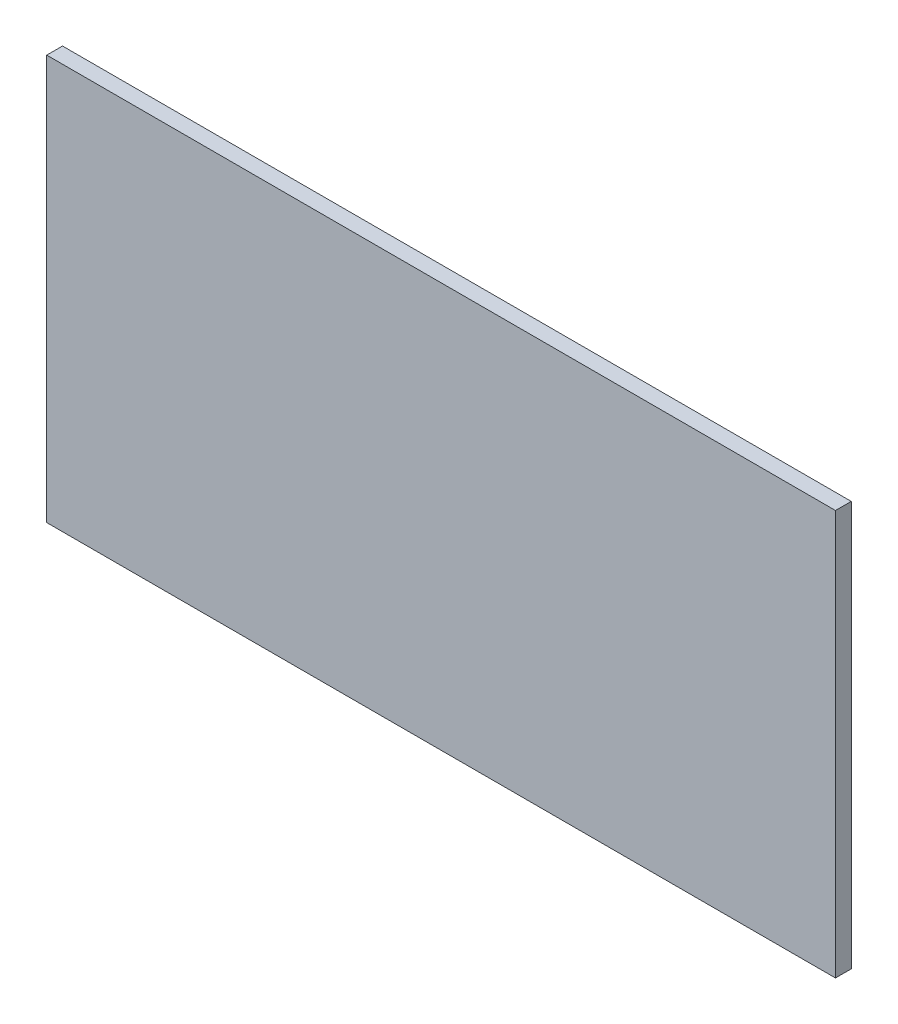
SolidWorks part; units mm, degrees
ref_plane "Спереди" through (0, 0, 0) normal (0, 0, 1) x (1, 0, 0)
ref_plane "Сверху" through (0, 0, 0) normal (0, 1, 0) x (1, 0, 0)
ref_plane "Справа" through (0, 0, 0) normal (1, 0, 0) x (0, 0, -1)
sketch "Эскиз1" plane through (0, 0, 0) normal (0, 0, 1) x (1, 0, 0)
  line L1 (-150, 77) -> (150, 77)
  line L2 (-150, 77) -> (-150, -77)
  line L3 (-150, -77) -> (150, -77)
  line L4 (150, 77) -> (150, -77)
  line L5 (-150, 77) -> (150, -77) construction
  line L6 (-150, -77) -> (150, 77) construction
  point P0 (0, 0)
  dimension "D1" = 154
  dimension "D2" = 300
extrude "Бобышка-Вытянуть1" add sketch "Эскиз1" along normal blind 6
